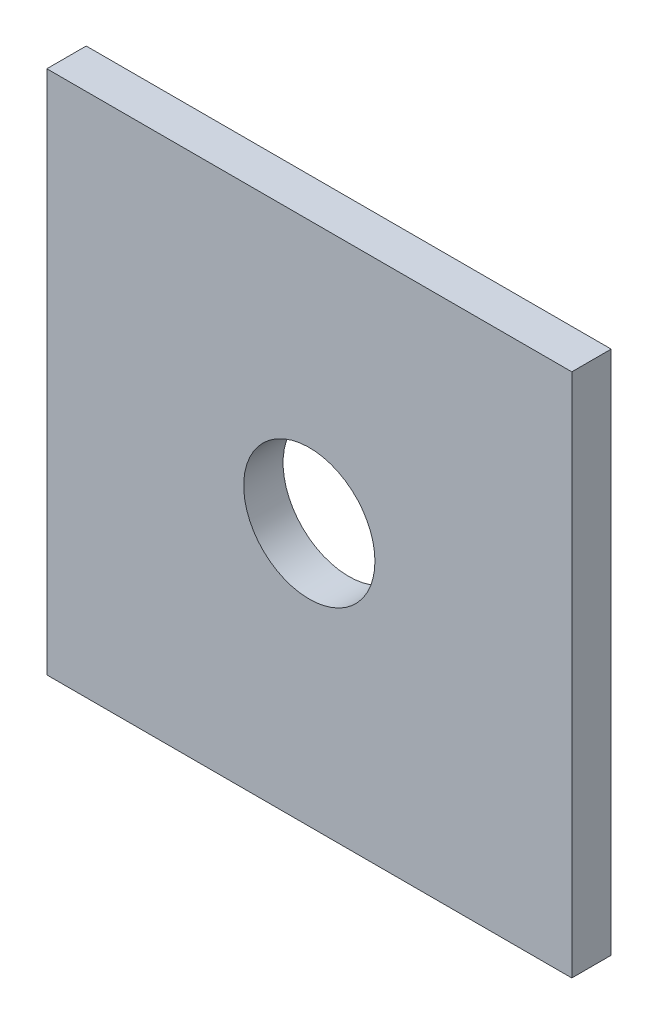
SolidWorks part; units mm, degrees
material "7075-T6 (SN)"
ref_plane "Alzado" through (0, 0, 0) normal (0, 0, 1) x (1, 0, 0)
ref_plane "Planta" through (0, 0, 0) normal (0, 1, 0) x (1, 0, 0)
ref_plane "Vista lateral" through (0, 0, 0) normal (1, 0, 0) x (0, 0, -1)
sketch "Croquis1" plane through (0, 0, 0) normal (0, 0, 1) x (1, 0, 0)
  line L1 (20, -20) -> (-20, -20)
  line L2 (20, -20) -> (20, 20)
  line L3 (20, 20) -> (-20, 20)
  line L4 (-20, -20) -> (-20, 20)
  line L5 (20, -20) -> (-20, 20) construction
  line L6 (20, 20) -> (-20, -20) construction
  circle A0 centre (0, 0) radius 5
  point P0 (0, 0)
  dimension "D2" = 10
  dimension "D1" = 40
extrude "Saliente-Extruir1" add sketch "Croquis1" along normal blind 3
